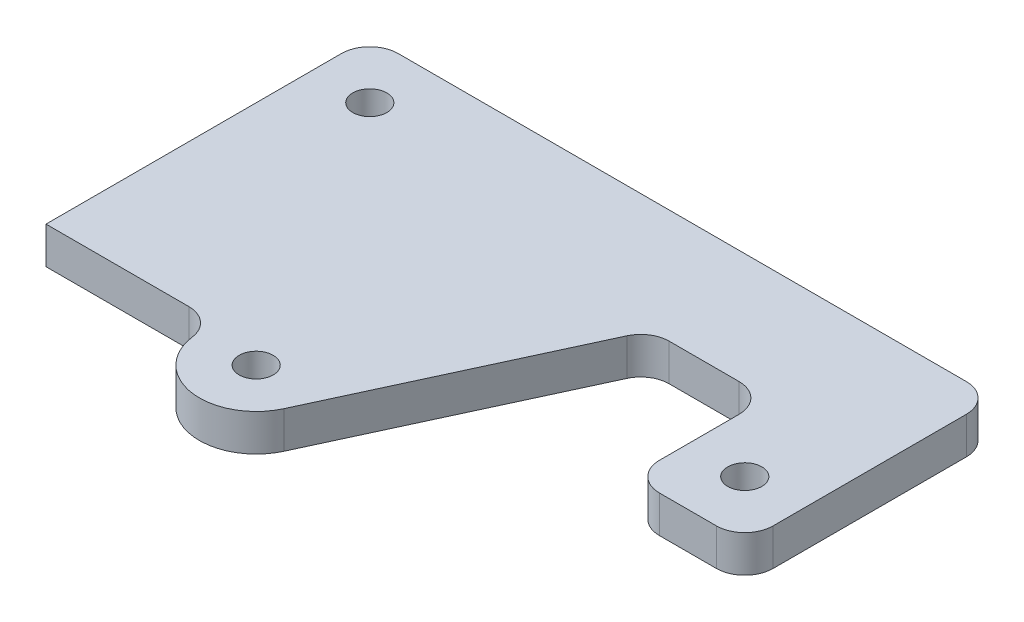
SolidWorks part; units mm, degrees
ref_plane "정면" through (0, 0, 0) normal (0, 0, 1) x (1, 0, 0)
ref_plane "윗면" through (0, 0, 0) normal (0, 1, 0) x (1, 0, 0)
ref_plane "우측면" through (0, 0, 0) normal (1, 0, 0) x (0, 0, -1)
sketch "스케치1" plane through (0, 0, 0) normal (0, 1, 0) x (1, 0, 0)
  line L0 (0, 0) -> (0, 52)
  line L1 (5, 57) -> (105, 57)
  line L2 (110, 52) -> (110, 18)
  line L3 (105, 13) -> (95, 13)
  line L4 (90, 18) -> (90, 32)
  line L5 (85, 37) -> (72.6939, 37)
  line L6 (68.155, 34.0971) -> (49.078, -7.1941)
  line L7 (0, 0) -> (25.1339, 0)
  arc A0 (30.0893, -4.3333) -> (49.078, -7.1941) centre (40, -3) ccw
  arc A1 (25.1339, 0) -> (30.0893, -4.3333) centre (25.1339, -5) cw
  arc A2 (0, 52) -> (5, 57) centre (5, 52) cw
  arc A3 (105, 57) -> (110, 52) centre (105, 52) cw
  arc A4 (110, 18) -> (105, 13) centre (105, 18) cw
  arc A5 (95, 13) -> (90, 18) centre (95, 18) cw
  arc A6 (90, 32) -> (85, 37) centre (85, 32) ccw
  arc A7 (72.6939, 37) -> (68.155, 34.0971) centre (72.6939, 32) ccw
  circle A8 centre (10, 47) radius 3
  circle A9 centre (40, -3) radius 3
  circle A10 centre (100, 23) radius 3
  point P15 (0, 57)
  point P18 (110, 57)
  point P21 (110, 13)
  point P24 (90, 13)
  point P34 (70, 36.2122)
  dimension "D8" = 20
  dimension "D9" = 5
  dimension "D10" = 5
  dimension "D11" = 5
  dimension "D12" = 5
  dimension "D13" = 5
  dimension "D18" = 6
  dimension "D19" = 6
  dimension "D20" = 6
  dimension "D1" = 57
  dimension "D2" = 110
  dimension "D3" = 44
  dimension "D4" = 20
  dimension "D5" = 20
  dimension "D6" = 60
  dimension "D7" = 40
  dimension "D14" = 10
  dimension "D15" = 10
  dimension "D16" = 10
  dimension "D17" = 10
  dimension "D21" = 70
extrude "보스-돌출1" add sketch "스케치1" along normal blind 6.5
